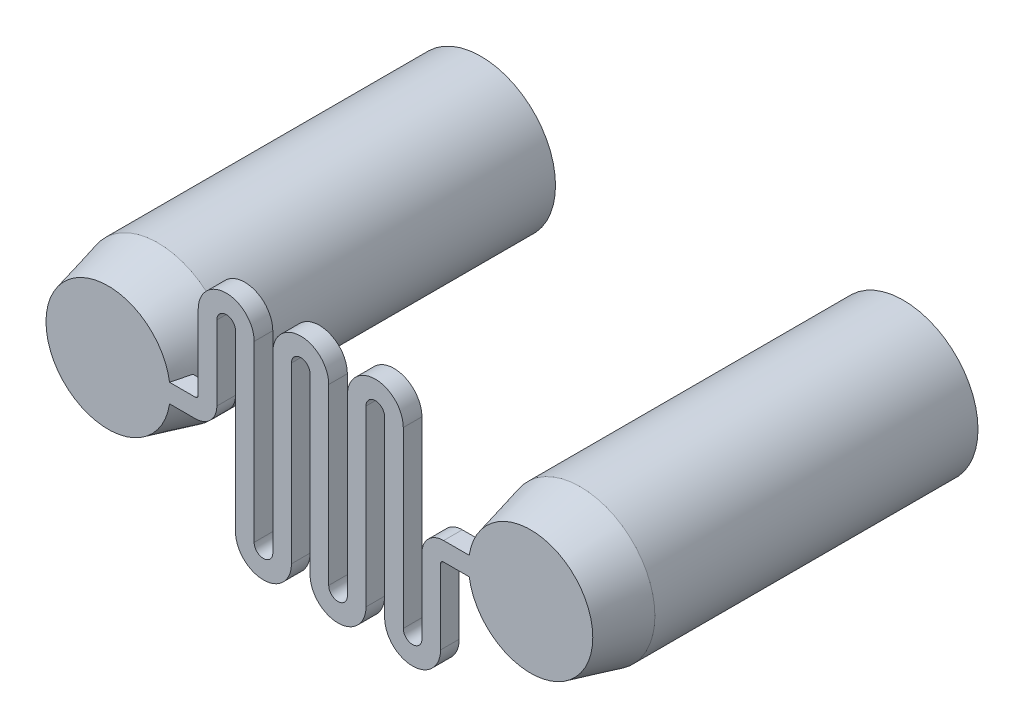
SolidWorks part; units mm, degrees
ref_plane "Front Plane" through (0, 0, 0) normal (0, 0, 1) x (1, 0, 0)
ref_plane "Top Plane" through (0, 0, 0) normal (0, 1, 0) x (1, 0, 0)
ref_plane "Right Plane" through (0, 0, 0) normal (1, 0, 0) x (0, 0, -1)
sketch "Sketch2" plane through (0, 0, 0) normal (0, 0, 1) x (1, 0, 0)
  line L3 (-20.5, -0.75) -> (-13.5, -0.75)
  line L6 (-11.75, 1) -> (-11.75, 7)
  line L9 (-10.25, 7) -> (-10.25, 0)
  line L12 (-10.25, 0) -> (-10.25, -7)
  line L15 (-5.75, -7) -> (-5.75, 0)
  line L18 (-5.75, 0) -> (-5.75, 7)
  line L21 (-4.25, 7) -> (-4.25, 0)
  line L22 (-4.25, 0) -> (-4.25, -7)
  line L23 (0.25, -7) -> (0.25, 0)
  line L24 (0.25, 0) -> (0.25, 7)
  line L25 (1.75, 7) -> (1.75, 0)
  line L26 (1.75, 0) -> (1.75, -7)
  line L27 (6.25, -7) -> (6.25, -1)
  line L28 (6.5, -0.75) -> (13.5, -0.75)
  line L29 (-20.5, 0.75) -> (-13.5, 0.75)
  line L30 (-13.25, 1) -> (-13.25, 7)
  line L31 (-8.75, 7) -> (-8.75, 0)
  line L32 (-8.75, 0) -> (-8.75, -7)
  line L33 (-7.25, -7) -> (-7.25, 0)
  line L34 (-7.25, 0) -> (-7.25, 7)
  line L35 (-2.75, 7) -> (-2.75, 0)
  line L36 (-2.75, 0) -> (-2.75, -7)
  line L37 (-1.25, -7) -> (-1.25, 0)
  line L38 (-1.25, 0) -> (-1.25, 7)
  line L39 (3.25, 7) -> (3.25, 0)
  line L40 (3.25, 0) -> (3.25, -7)
  line L41 (4.75, -7) -> (4.75, -1)
  line L42 (6.5, 0.75) -> (13.5, 0.75)
  arc A8 (-11.75, 1) -> (-13.5, -0.75) centre (-13.5, 1) cw
  arc A9 (-11.75, 7) -> (-10.25, 7) centre (-11, 7) cw
  arc A10 (-10.25, -7) -> (-5.75, -7) centre (-8, -7) ccw
  arc A11 (-5.75, 7) -> (-4.25, 7) centre (-5, 7) cw
  arc A12 (-4.25, -7) -> (0.25, -7) centre (-2, -7) ccw
  arc A13 (0.25, 7) -> (1.75, 7) centre (1, 7) cw
  arc A14 (1.75, -7) -> (6.25, -7) centre (4, -7) ccw
  arc A15 (6.25, -1) -> (6.5, -0.75) centre (6.5, -1) cw
  arc A16 (-13.25, 1) -> (-13.5, 0.75) centre (-13.5, 1) cw
  arc A17 (-13.25, 7) -> (-8.75, 7) centre (-11, 7) cw
  arc A18 (-8.75, -7) -> (-7.25, -7) centre (-8, -7) ccw
  arc A19 (-7.25, 7) -> (-2.75, 7) centre (-5, 7) cw
  arc A20 (-2.75, -7) -> (-1.25, -7) centre (-2, -7) ccw
  arc A21 (-1.25, 7) -> (3.25, 7) centre (1, 7) cw
  arc A22 (3.25, -7) -> (4.75, -7) centre (4, -7) ccw
  arc A23 (4.75, -1) -> (6.5, 0.75) centre (6.5, -1) cw
  arc A24 (13.5, -0.75) -> (13.5, 0.75) centre (13.5, 0) ccw
  arc A25 (-20.5, 0.75) -> (-20.5, -0.75) centre (-20.5, 0) ccw
  point P4 (0, 0)
  point P32 (5.5, 0)
  point P35 (-12.5, 0)
  dimension "D1" = 8
  dimension "D14" = 8
extrude "Boss-Extrude1" add sketch "Sketch2" along normal blind 1.5
ref_plane "Plane1" through (0, 0, 0) normal (0, 1, 0) x (1, 0, 0)
sketch "Sketch3" plane through (0, 0, 0) normal (0, 1, 0) x (1, 0, 0)
  line L0 (-20.5, -1.5) -> (-25.5, -1.5)
  line L2 (-20.5, -1.5) -> (-20.5, 28.5)
  line L3 (-20.5, 28.5) -> (-26.5, 28.5)
  line L4 (-26.5, 28.5) -> (-26.5, 2.5)
  line L5 (-26.5, 2.5) -> (-25.5, -1.5)
  dimension "D1" = 5
  dimension "D3" = 30
  dimension "D4" = 6
revolve "Revolve1" add sketch "Sketch3" angle 360 about L2
ref_plane "Plane2" through (0, 0, 0) normal (0, 1, 0) x (1, 0, 0)
sketch "Sketch4" plane through (0, 0, 0) normal (0, 1, 0) x (1, 0, 0)
  line L0 (13.5, -1.5) -> (18.5, -1.5)
  line L2 (13.5, -1.5) -> (13.5, 28.5)
  line L3 (13.5, 28.5) -> (19.5, 28.5)
  line L4 (19.5, 28.5) -> (19.5, 2.5)
  line L5 (19.5, 2.5) -> (18.5, -1.5)
  dimension "D1" = 5
  dimension "D3" = 30
  dimension "D4" = 6
revolve "Revolve2" add sketch "Sketch4" angle 360 about L2
sketch "Sketch5" plane through (0, 0, -28.5) normal (0, 0, -1) x (-1, 0, 0)
  circle A0 centre (-13.5, 0) radius 5
  circle A1 centre (20.5, 0) radius 5
  dimension "D1" = 10
  dimension "D2" = 10
extrude "Cut-Extrude1" cut sketch "Sketch5" against normal blind 28
